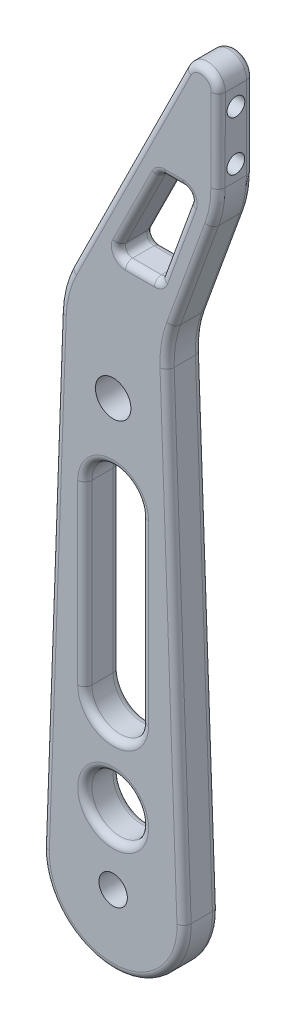
SolidWorks part; units mm, degrees
ref_plane "Front Plane" through (0, 0, 0) normal (0, 0, 1) x (1, 0, 0)
ref_plane "Top Plane" through (0, 0, 0) normal (0, 1, 0) x (1, 0, 0)
ref_plane "Right Plane" through (0, 0, 0) normal (1, 0, 0) x (0, 0, -1)
sketch "Sketch1" plane through (0, 0, 0) normal (0, 0, 1) x (1, 0, 0)
  line L0 (0, 149.1168) -> (0, 12) construction
  line L1 (-15, 140) -> (-19.9872, 0.7157)
  line L2 (15, 140) -> (29.5588, 180)
  line L3 (15, 140) -> (19.9872, 0.7157)
  line L4 (29.5588, 180) -> (29.6982, 229.9998)
  line L5 (29.6982, 229.9998) -> (-15, 140)
  line L6 (-149.8827, 140) -> (181.2115, 140) construction
  line L7 (0, 95) -> (0, 45) construction
  line L8 (8, 95) -> (8, 45)
  line L9 (-8, 95) -> (-8, 45)
  line L10 (0.2655, 155) -> (13.2994, 181.2437)
  line L11 (22.5622, 181.2437) -> (13.2994, 181.2437)
  line L12 (22.5622, 181.2437) -> (13.0103, 155)
  line L13 (0.2655, 155) -> (13.0103, 155)
  arc A0 (-19.9872, 0.7157) -> (19.9872, 0.7157) centre (0, 0) ccw
  arc A1 (8, 95) -> (-8, 95) centre (0, 95) ccw
  arc A2 (-8, 45) -> (8, 45) centre (0, 45) ccw
  circle A3 centre (0, 0) radius 4
  circle A4 centre (0, 20) radius 8
  circle A5 centre (0, 120) radius 5
  point P5 (0, 70)
  point P20 (0, -20)
  dimension "D2" = 40
  dimension "D6" = 70
  dimension "D3" = 7
  dimension "D16" = 20
  dimension "D10" = 20
  dimension "D15" = 25
  dimension "D4" = 15
  dimension "D5" = 15
  dimension "D7" = 40
  dimension "D8" = 50
  dimension "D9" = 7
  dimension "D11" = 15
  dimension "D12" = 160
  dimension "D13" = 50
  dimension "D14" = 15
  dimension "D17" = 25
extrude "Boss-Extrude1" add sketch "Sketch1" along normal blind 10
fillet "Fillet1" radius 5 1 edges at (29.6982, 229.9998, 5)
fillet "Fillet2" radius 30 3 edges at (29.5588, 180, 5) (15, 140, 5) (-15, 140, 5)
sketch "Sketch2" plane through (29.0568, -0.081, 0) normal (1, -0.0028, 0) x (0, 0, -1)
  line L0 (0, 208.6391) -> (-10, 208.6391) construction
  circle A0 centre (-5, 203.6391) radius 2.5
  circle A1 centre (-5, 189.6391) radius 2.5
  point P6 (-5, 208.6391)
  dimension "D3" = 5
  dimension "D4" = 5
  dimension "D1" = 5
  dimension "D2" = 14
extrude "Cut-Extrude1" cut sketch "Sketch2" against normal blind 21
fillet "Fillet3" radius 2 42 edges at (17.9308, 181.2437, 10) (17.9308, 181.2437, 0) (-8, 70, 0) (0, 103, 0) (8, 70, 0) (-8, 70, 10) (0, 103, 10) (8, 70, 10) (0, -20, 0) (-17.6095, 67.1222, 0) (-14.3303, 139.8302, 0) (4.0203, 178.2974, 0) (25.7875, 213.4374, 0) (29.6059, 196.902, 0) (29.1105, 180.0797, 0) (22.3817, 160.2812, 0) (15.5572, 139.912, 0) (0, -20, 10) (-17.6095, 67.1222, 10) (-14.3303, 139.8302, 10) (4.0203, 178.2974, 10) (25.7875, 213.4374, 10) (29.6059, 196.902, 10) (29.1105, 180.0797, 10) (22.3817, 160.2812, 10) (15.5572, 139.912, 10) (8, 20, 0) (8, 20, 10) (13.0103, 155, 5) (0.2655, 155, 5) (13.2994, 181.2437, 5) (22.5622, 181.2437, 5) (17.7863, 168.1219, 10) (17.7863, 168.1219, 0) (6.7824, 168.1219, 10) (6.7824, 168.1219, 0) (6.6379, 155, 0) (6.6379, 155, 10) (0, 37, 0) (0, 37, 10) (17.5982, 67.4371, 0) (17.5982, 67.4371, 10)
